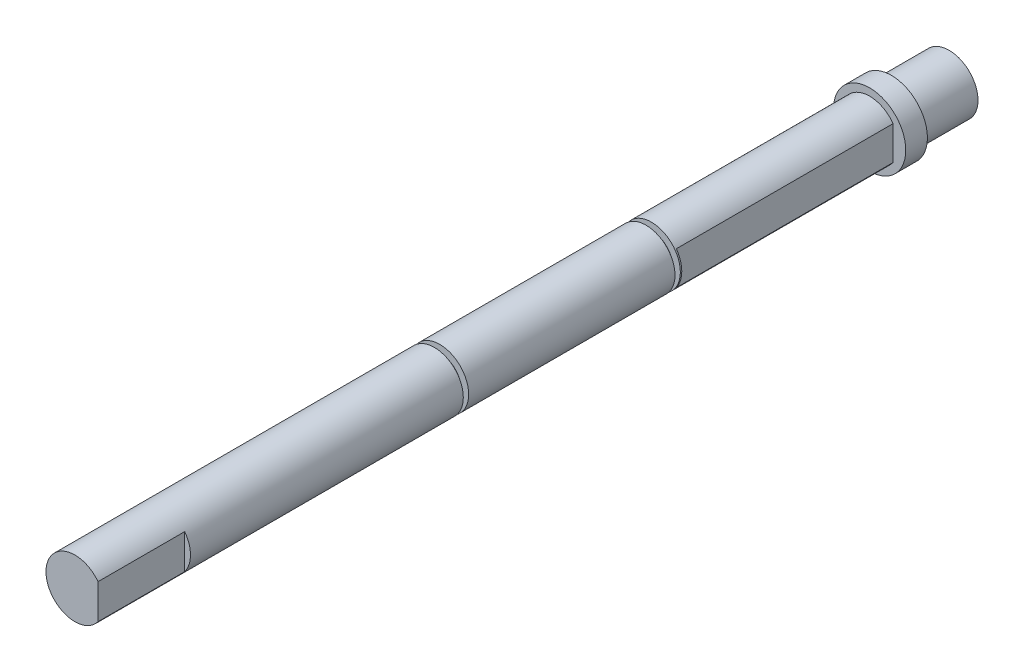
SolidWorks part; units mm, degrees
ref_plane "Front Plane" through (0, 0, 0) normal (0, 0, 1) x (1, 0, 0)
ref_plane "Top Plane" through (0, 0, 0) normal (0, 1, 0) x (1, 0, 0)
ref_plane "Right Plane" through (0, 0, 0) normal (1, 0, 0) x (0, 0, -1)
sketch "Sketch1" plane through (0, 0, 0) normal (0, 0, 1) x (1, 0, 0)
  circle A0 centre (0, 0) radius 4
extrude "Lower_seat" add sketch "Sketch1" along normal blind 8
ref_plane "Plane_z8" through (0, 0, 8) normal (0, 0, 1) x (1, 0, 0)
sketch "Sketch2" plane through (0, 0, 8) normal (0, 0, 1) x (1, 0, 0)
  circle A0 centre (0, 0) radius 5
extrude "Collar" add sketch "Sketch2" along normal blind 3
ref_plane "Plane_z11" through (0, 0, 11) normal (0, 0, 1) x (1, 0, 0)
sketch "Sketch3" plane through (0, 0, 11) normal (0, 0, 1) x (1, 0, 0)
  circle A0 centre (0, 0) radius 4
extrude "Upper" add sketch "Sketch3" along normal blind 110
ref_plane "Plane_z41_2" through (0, 0, 41.2) normal (0, 0, 1) x (1, 0, 0)
sketch "Sketch4" plane through (0, 0, 41.2) normal (0, 0, 1) x (1, 0, 0)
  circle A0 centre (0, 0) radius 5
  circle A1 centre (0, 0) radius 3
extrude "Eclip_groove1" cut sketch "Sketch4" along normal blind 0.74
ref_plane "Plane_z70_5" through (0, 0, 70.5) normal (0, 0, 1) x (1, 0, 0)
sketch "Sketch5" plane through (0, 0, 70.5) normal (0, 0, 1) x (1, 0, 0)
  circle A0 centre (0, 0) radius 5
  circle A1 centre (0, 0) radius 3
extrude "Eclip_groove2" cut sketch "Sketch5" along normal blind 0.74
sketch "Sketch6" plane through (0, 0, 11) normal (0, 0, 1) x (1, 0, 0)
  line L1 (3.25, -5) -> (6.25, -5)
  line L2 (3.25, -5) -> (3.25, 5)
  line L3 (3.25, 5) -> (6.25, 5)
  line L4 (6.25, -5) -> (6.25, 5)
  line L6 (-6.25, -5) -> (-3.25, -5)
  line L7 (-6.25, -5) -> (-6.25, 5)
  line L8 (-6.25, 5) -> (-3.25, 5)
  line L9 (-3.25, -5) -> (-3.25, 5)
extrude "Burr_flats" cut sketch "Sketch6" along normal blind 30
ref_plane "Plane_z109" through (0, 0, 109) normal (0, 0, 1) x (1, 0, 0)
sketch "Sketch7" plane through (0, 0, 109) normal (0, 0, 1) x (1, 0, 0)
  line L1 (3.2, -5) -> (6.2, -5)
  line L2 (3.2, -5) -> (3.2, 5)
  line L3 (3.2, 5) -> (6.2, 5)
  line L4 (6.2, -5) -> (6.2, 5)
extrude "Crank_flat" cut sketch "Sketch7" along normal blind 12
